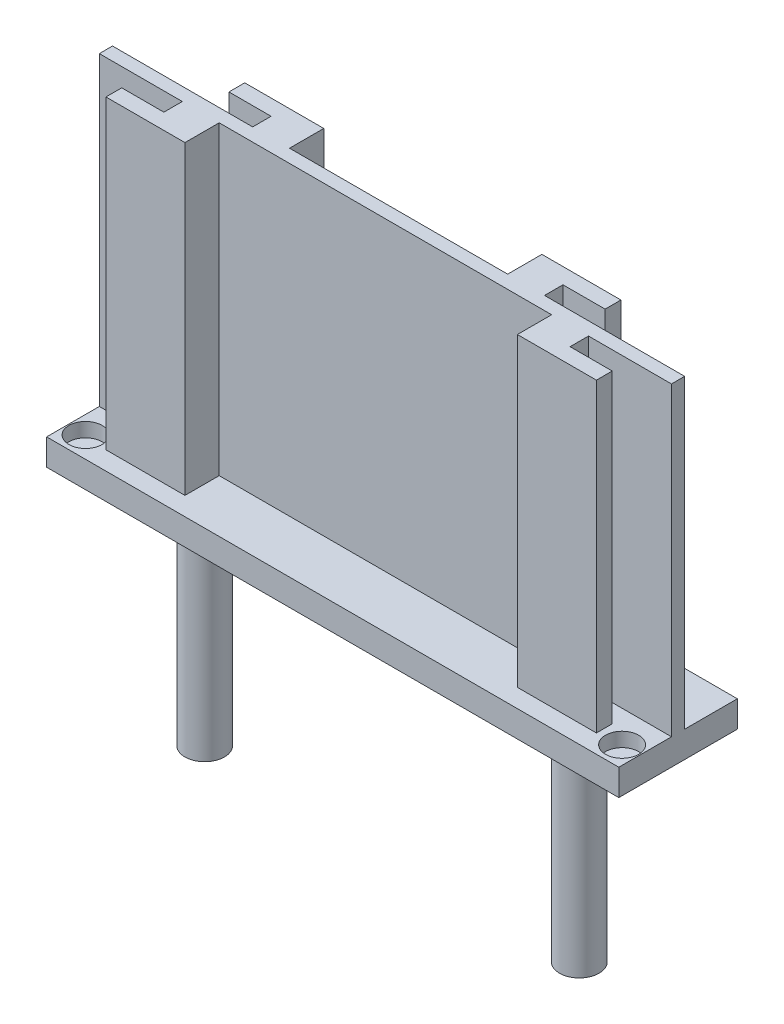
SolidWorks part; units mm, degrees
material "eSUN Tough Resin"
ref_plane "Front Plane" through (0, 0, 0) normal (0, 0, 1) x (1, 0, 0)
ref_plane "Top Plane" through (0, 0, 0) normal (0, 1, 0) x (1, 0, 0)
ref_plane "Right Plane" through (0, 0, 0) normal (1, 0, 0) x (0, 0, -1)
sketch "Sketch1" plane through (0, 0, 0) normal (0, 1, 0) x (1, 0, 0)
  line L1 (-54.3, -11.25) -> (54.3, -11.25)
  line L2 (-54.3, -11.25) -> (-54.3, 11.25)
  line L3 (-54.3, 11.25) -> (54.3, 11.25)
  line L4 (54.3, -11.25) -> (54.3, 11.25)
  line L5 (-54.3, -11.25) -> (54.3, 11.25) construction
  line L6 (-54.3, 11.25) -> (54.3, -11.25) construction
  point P0 (0, 0)
  dimension "D1" = 108.6
  dimension "D2" = 22.5
extrude "Boss-Extrude1" add sketch "Sketch1" along normal blind 5
sketch "Sketch2" plane through (0, 5, 0) normal (0, 1, 0) x (1, 0, 0)
  line L0 (-54.3, -11.25) -> (54.3, -11.25) construction
  line L2 (54.3, 11.25) -> (-54.3, 11.25) construction
  line L3 (0, 11.25) -> (0, -11.25) construction
  circle A4 centre (50.925, -7.25) radius 3.15 construction
  circle A5 centre (40.075, 7.25) radius 3.15 construction
  circle A6 centre (-50.925, -7.25) radius 3.15 construction
  circle A7 centre (-40.075, 7.25) radius 3.15 construction
  circle A8 centre (50.925, -7.25) radius 3.15
  circle A9 centre (40.075, 7.25) radius 3.15
  circle A10 centre (-50.925, -7.25) radius 3.15
  circle A11 centre (-40.075, 7.25) radius 3.15
extrude "Cut-Extrude1" cut sketch "Sketch2" against normal blind 2.7
sketch "Sketch3" plane through (0, 5, 0) normal (0, 1, 0) x (1, 0, 0)
  line L0 (-54.3, 0) -> (54.3, 0) construction
  line L1 (-54.3, 11.25) -> (-54.3, -11.25) construction
  line L2 (54.3, -11.25) -> (54.3, 11.25) construction
  line L3 (-38.55, -1.25) -> (-38.55, -4.75)
  line L4 (-54.3, 1.25) -> (54.3, 1.25)
  line L5 (-54.3, 1.25) -> (-54.3, -1.25)
  line L6 (-54.3, -1.25) -> (54.3, -1.25)
  line L7 (54.3, 1.25) -> (54.3, -1.25)
  line L8 (-38.55, -4.75) -> (-46.55, -4.75)
  line L9 (-46.55, -4.75) -> (-46.55, -7.75)
  line L14 (-46.55, -7.75) -> (-31.55, -7.75)
  line L15 (-31.55, -7.75) -> (-31.55, -1.25)
  line L16 (-38.55, -1.25) -> (-31.55, -1.25)
  line L17 (-27.7, 1.25) -> (-27.7, 4.75)
  line L18 (-27.7, 4.75) -> (-35.7, 4.75)
  line L19 (-35.7, 4.75) -> (-35.7, 7.75)
  line L24 (-35.7, 7.75) -> (-20.7, 7.75)
  line L25 (-20.7, 7.75) -> (-20.7, 1.25)
  line L26 (-27.7, 1.25) -> (-20.7, 1.25)
  point P10 (-54.3, 0)
  dimension "D1" = 2.5
  dimension "D2" = 3
  dimension "D3" = 8
  dimension "D4" = 7.75
  dimension "D5" = 3.5
  dimension "D7" = 22.75
  dimension "D10" = 3.5
  dimension "D11" = 3
  dimension "D12" = 18.6
  dimension "D13" = 33.6
  dimension "D16" = 8
extrude "Boss-Extrude2" add sketch "Sketch3" along normal blind 58
ref_plane "Plane1" through (0, 0, 0) normal (1, 0, 0) x (0, 0, -1)
mirror "Mirror1" about plane through (0, 0, 0) normal (1, 0, 0) of "Boss-Extrude2"
sketch "Sketch4" plane through (0, 0, 0) normal (0, -1, 0) x (1, 0, 0)
  line L0 (-54.3, -11.25) -> (-54.3, 11.25) construction
  line L2 (54.3, 11.25) -> (54.3, -11.25) construction
  circle A0 centre (-35.55, 0) radius 1.5
  circle A1 centre (35.55, 0) radius 1.5
  circle A2 centre (-35.55, 0) radius 3.75
  circle A3 centre (35.55, 0) radius 3.75
  dimension "D3" = 3
  dimension "D4" = 3
  dimension "D5" = 7.5
  dimension "D6" = 7.5
  dimension "D1" = 18.75
  dimension "D2" = 18.75
  dimension "D7" = 71.1
extrude "Boss-Extrude3" add sketch "Sketch4" along normal blind 42
fillet "Fillet1" radius 1 2 edges at (35.55, 0, -3.75) (-35.55, 0, -3.75)
